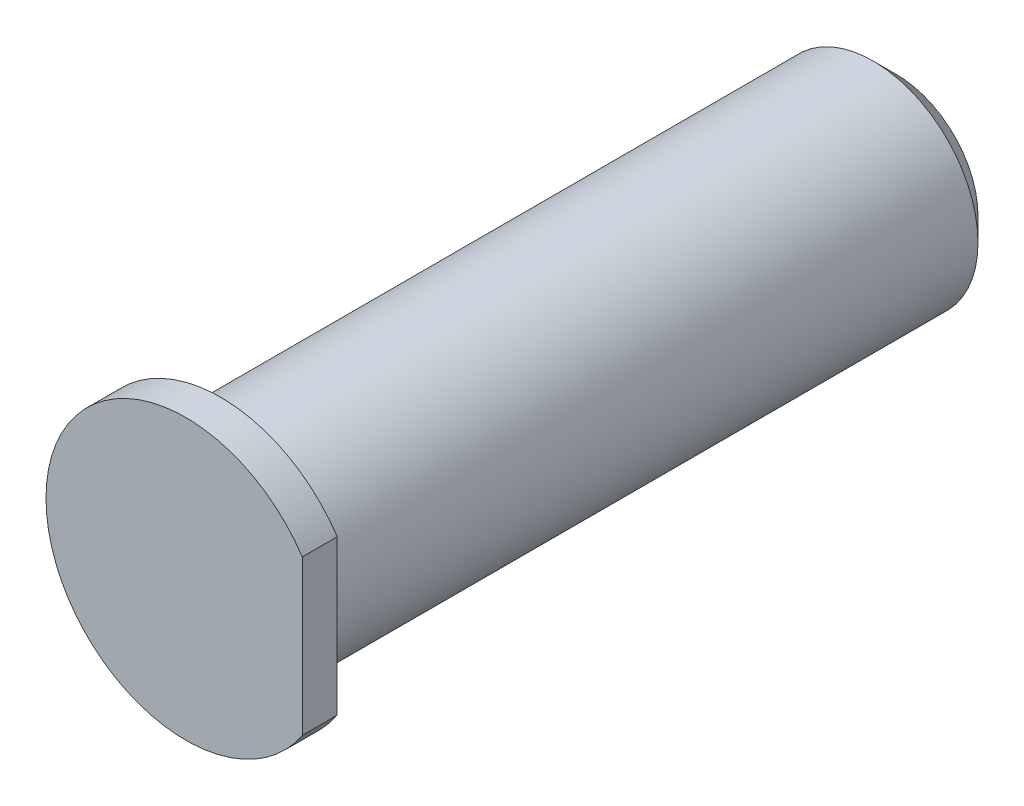
SolidWorks part; units mm, degrees
ref_plane "Plan1" through (0, 0, 0) normal (0, 0, 1) x (1, 0, 0)
ref_plane "Plan2" through (0, 0, 0) normal (0, 1, 0) x (1, 0, 0)
ref_plane "Plan3" through (0, 0, 0) normal (1, 0, 0) x (0, 0, -1)
sketch "Esquisse_cylindre" plane through (0, 0, 0) normal (0, 0, 1) x (1, 0, 0)
  circle A0 centre (0, 0) radius 4.5
  dimension "D1" = 9
extrude "Cylindre" add sketch "Esquisse_cylindre" against normal blind 29
sketch "Esquisse_épaulement" plane through (0, 0, 0) normal (0, 0, 1) x (1, 0, 0)
  line L0 (5, 3.3166) -> (5, -3.3166)
  arc A0 (5, 3.3166) -> (5, -3.3166) centre (0, 0) ccw
  dimension "D1" = 12
  dimension "D2" = 5
extrude "Epaulement" add sketch "Esquisse_épaulement" along normal blind 1.5
sketch "Esquisse_trou" plane through (0, 0, -29) normal (0, 0, -1) x (-1, 0, 0)
  circle A0 centre (0, 0) radius 2
  dimension "D1" = 4
extrude "Trou" cut sketch "Esquisse_trou" against normal blind 3.5
chamfer "Chanfrein1" distance 1 angle 45
